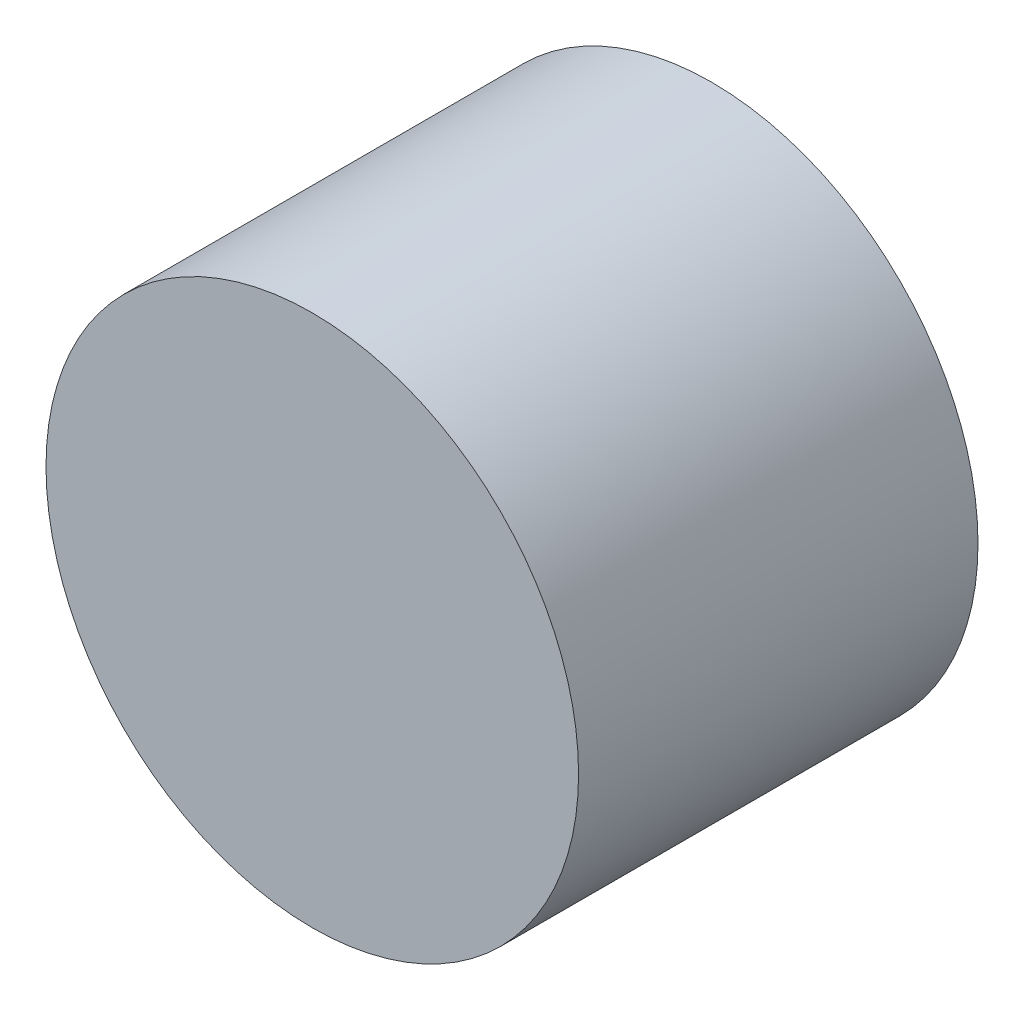
SolidWorks part; units mm, degrees
ref_plane "Face" through (0, 0, 0) normal (0, 0, 1) x (1, 0, 0)
ref_plane "Dessus" through (0, 0, 0) normal (0, 1, 0) x (1, 0, 0)
ref_plane "Droite" through (0, 0, 0) normal (1, 0, 0) x (0, 0, -1)
sketch "Esquisse1" plane through (0, 0, 0) normal (0, 0, 1) x (1, 0, 0)
  circle A0 centre (0, 0) radius 4
  dimension "D1" = 8
extrude "Base-Extrusion" add sketch "Esquisse1" along normal blind 6
